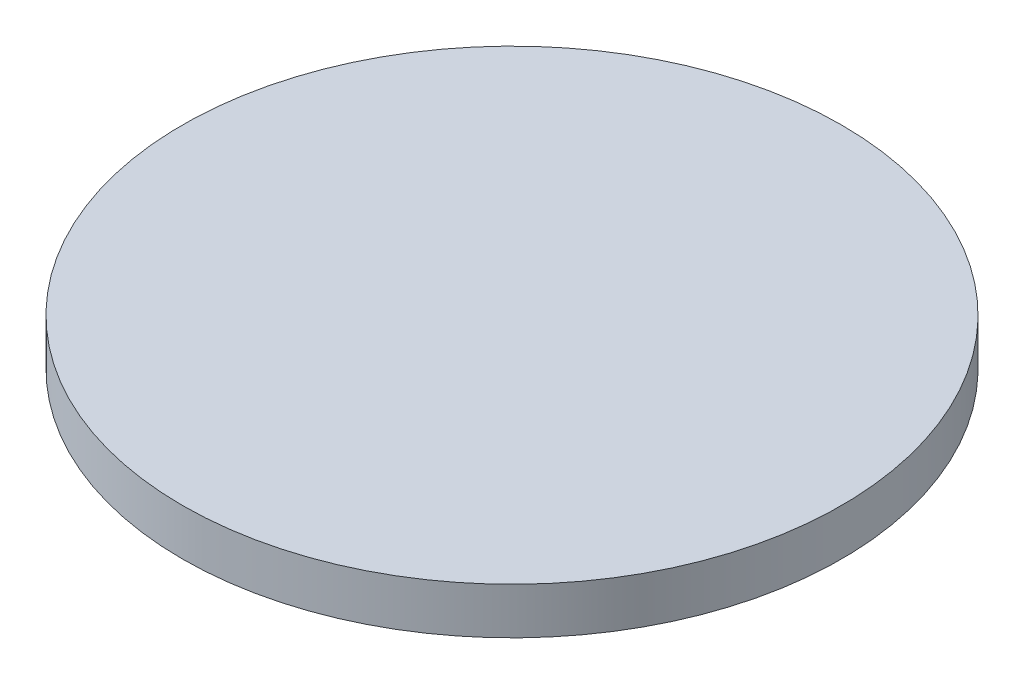
SolidWorks part; units mm, degrees
ref_plane "Front Plane" through (0, 0, 0) normal (0, 0, 1) x (1, 0, 0)
ref_plane "Top Plane" through (0, 0, 0) normal (0, 1, 0) x (1, 0, 0)
ref_plane "Right Plane" through (0, 0, 0) normal (1, 0, 0) x (0, 0, -1)
ref_plane "PY_p28_40" through (0, 28.4, 0) normal (0, 1, 0) x (1, 0, 0)
sketch "PCB_Sk1" plane through (0, 28.4, 0) normal (0, 1, 0) x (1, 0, 0)
  circle A0 centre (16, 22.5) radius 7.1
extrude "PCB" add sketch "PCB_Sk1" against normal blind 1
ref_plane "PY_p27_40" through (0, 27.4, 0) normal (0, 1, 0) x (1, 0, 0)
sketch "Mic_Sk2" plane through (0, 27.4, 0) normal (0, 1, 0) x (1, 0, 0)
  line L0 (13.64, 24.38) -> (18.36, 24.38)
  line L1 (18.36, 24.38) -> (18.36, 20.62)
  line L2 (18.36, 20.62) -> (13.64, 20.62)
  line L3 (13.64, 20.62) -> (13.64, 24.38)
extrude "Mic" add sketch "Mic_Sk2" against normal blind 1.1
